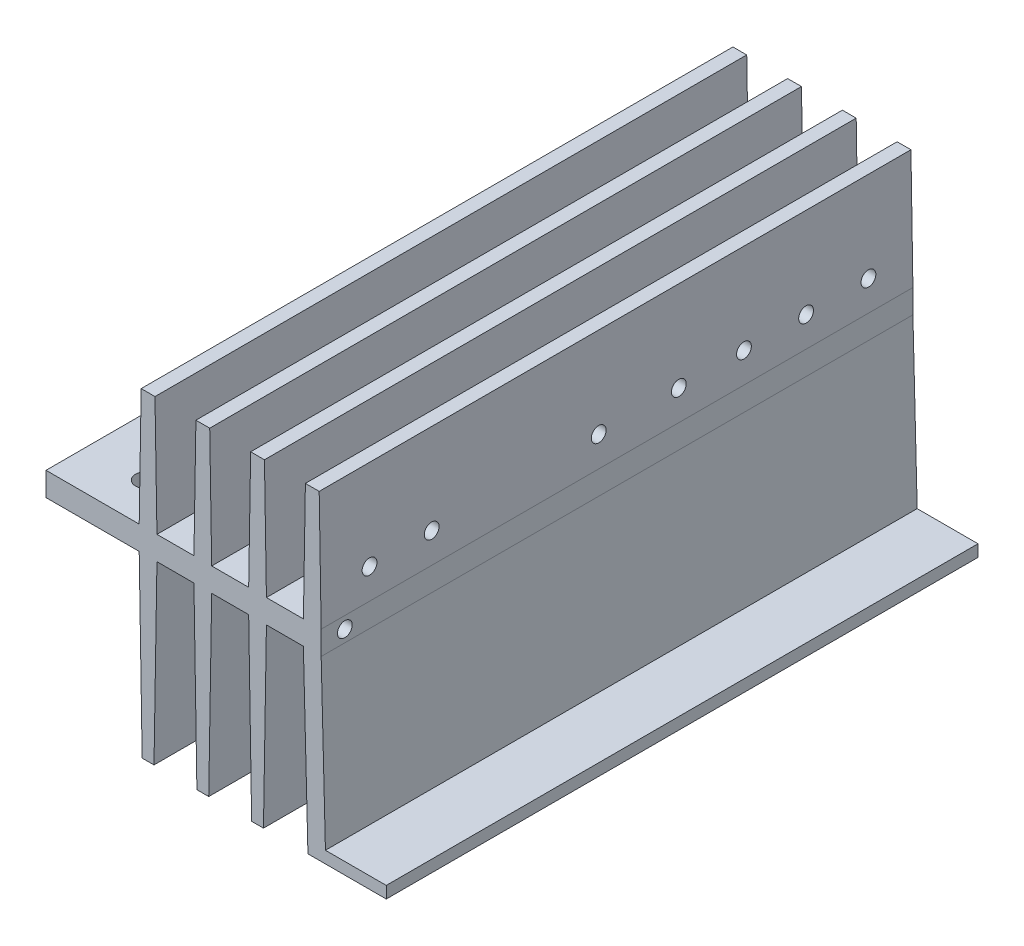
SolidWorks part; units mm, degrees
ref_plane "Front Plane" through (0, 0, 0) normal (0, 0, 1) x (1, 0, 0)
ref_plane "Top Plane" through (0, 0, 0) normal (0, 1, 0) x (1, 0, 0)
ref_plane "Right Plane" through (0, 0, 0) normal (1, 0, 0) x (0, 0, -1)
sketch "Skica1" plane through (0, 0, 0) normal (0, 0, 1) x (1, 0, 0)
  line L0 (7.579, 64.9717) -> (122.579, 64.9717) construction
  line L1 (7.2899, 64.6896) -> (122.2899, 64.6896) construction
  line L2 (64.7899, 64.6896) -> (64.7899, 137.3686) construction
  line L3 (111.2899, 94.6896) -> (18.2899, 94.6896)
  line L4 (18.2899, 98.6896) -> (111.2899, 98.6896)
  line L5 (18.2899, 94.6896) -> (17.5681, 66.6896)
  line L6 (17.5681, 66.6896) -> (7.2899, 66.6896)
  line L7 (7.2899, 66.6896) -> (7.2899, 64.6896)
  line L8 (7.2899, 64.6896) -> (20.5245, 64.6896)
  line L9 (20.5245, 64.6896) -> (21.298, 94.6896)
  line L10 (18.2899, 94.6896) -> (18.2899, 98.6896)
  line L11 (18.2899, 98.6896) -> (18.7899, 128.6896)
  line L12 (18.7899, 128.6896) -> (20.7899, 128.6896)
  line L13 (20.7899, 128.6896) -> (21.2899, 98.6896)
  line L14 (19.7899, 98.6896) -> (19.7899, 132.7731) construction
  line L15 (27.5399, 98.6896) -> (28.0399, 128.6896)
  line L16 (28.0399, 128.6896) -> (30.0399, 128.6896)
  line L17 (30.0399, 128.6896) -> (30.5399, 98.6896)
  line L18 (36.7899, 98.6896) -> (37.2899, 128.6896)
  line L19 (37.2899, 128.6896) -> (39.2899, 128.6896)
  line L20 (39.2899, 128.6896) -> (39.7899, 98.6896)
  line L21 (46.0399, 98.6896) -> (46.5399, 128.6896)
  line L22 (46.5399, 128.6896) -> (48.5399, 128.6896)
  line L23 (48.5399, 128.6896) -> (49.0399, 98.6896)
  line L24 (18.2899, 96.6896) -> (15.4654, 96.6896) construction
  line L25 (48.5399, 64.6896) -> (49.0399, 94.6896)
  line L26 (46.0399, 94.6896) -> (46.5399, 64.6896)
  line L27 (46.5399, 64.6896) -> (48.5399, 64.6896)
  line L28 (39.2899, 64.6896) -> (39.7899, 94.6896)
  line L29 (37.2899, 64.6896) -> (39.2899, 64.6896)
  line L30 (36.7899, 94.6896) -> (37.2899, 64.6896)
  line L31 (30.0399, 64.6896) -> (30.5399, 94.6896)
  line L32 (28.0399, 64.6896) -> (30.0399, 64.6896)
  line L33 (27.5399, 94.6896) -> (28.0399, 64.6896)
  line L34 (111.2899, 96.6896) -> (114.1145, 96.6896) construction
  line L35 (109.7899, 98.6896) -> (109.7899, 132.7731) construction
  line L36 (102.0399, 94.6896) -> (101.5399, 64.6896)
  line L37 (101.5399, 64.6896) -> (99.5399, 64.6896)
  line L38 (99.5399, 64.6896) -> (99.0399, 94.6896)
  line L39 (92.7899, 94.6896) -> (92.2899, 64.6896)
  line L40 (92.2899, 64.6896) -> (90.2899, 64.6896)
  line L41 (90.2899, 64.6896) -> (89.7899, 94.6896)
  line L42 (83.0399, 64.6896) -> (81.0399, 64.6896)
  line L43 (83.5399, 94.6896) -> (83.0399, 64.6896)
  line L44 (81.0399, 64.6896) -> (80.5399, 94.6896)
  line L45 (81.0399, 128.6896) -> (80.5399, 98.6896)
  line L46 (83.0399, 128.6896) -> (81.0399, 128.6896)
  line L47 (83.5399, 98.6896) -> (83.0399, 128.6896)
  line L48 (90.2899, 128.6896) -> (89.7899, 98.6896)
  line L49 (92.2899, 128.6896) -> (90.2899, 128.6896)
  line L50 (92.7899, 98.6896) -> (92.2899, 128.6896)
  line L51 (99.5399, 128.6896) -> (99.0399, 98.6896)
  line L52 (101.5399, 128.6896) -> (99.5399, 128.6896)
  line L53 (102.0399, 98.6896) -> (101.5399, 128.6896)
  line L54 (108.7899, 128.6896) -> (108.2899, 98.6896)
  line L55 (110.7899, 128.6896) -> (108.7899, 128.6896)
  line L56 (111.2899, 98.6896) -> (110.7899, 128.6896)
  line L57 (111.2899, 94.6896) -> (111.2899, 98.6896)
  line L58 (109.0553, 64.6896) -> (108.2819, 94.6896)
  line L59 (122.2899, 64.6896) -> (109.0553, 64.6896)
  line L60 (122.2899, 66.6896) -> (122.2899, 64.6896)
  line L61 (112.0118, 66.6896) -> (122.2899, 66.6896)
  line L62 (111.2899, 94.6896) -> (112.0118, 66.6896)
  point P46 (64.7899, 94.6896)
  point P47 (64.7899, 98.6896)
  dimension "D1" = 115
  dimension "D2" = 115
  dimension "D3" = 3
  dimension "D4" = 2
  dimension "D5" = 1.5
  dimension "D6" = 1
  dimension "D7" = 4
  dimension "D8" = 2
  dimension "D9" = 30
  dimension "D10" = 11
  dimension "D11" = 64
  dimension "D12" = 4
extrude "Přidat vysunutím1" add sketch "Skica1" along normal blind 100 contours L44 L42 L43 L3 | L41 L40 L39 L3 | L38 L37 L36 L3 | L62 L3 L58 L59 L60 L61 | L4 L56 L55 L54 | L4 L53 L52 L51 | L4 L50 L49 L48 | L4 L47 L46 L45 | L3 L57 L4 L10 | L17 L16 L15 L4 | L20 L19 L18 L4 | L23 L22 L21 L4 | L13 L12 L11 L4 | L8 L9 L3 L5 L6 L7 | L3 L33 L32 L31 | L3 L30 L29 L28 | L26 L27 L25 L3
sketch "Skica2" plane through (0, 0, 100) normal (0, 0, 1) x (1, 0, 0)
  line L0 (18.7899, 128.6896) -> (20.7899, 128.6896) construction
  line L1 (8.3667, 139.0565) -> (129.8572, 139.0565)
  line L2 (8.3667, 139.0565) -> (8.3667, 118.6896)
  line L3 (8.3667, 118.6896) -> (129.8572, 118.6896)
  line L4 (129.8572, 139.0565) -> (129.8572, 118.6896)
  dimension "D1" = 10
extrude "Odebrat vysunutím1" cut sketch "Skica2" against normal through all
sketch "Skica3" plane through (0, 0, 100) normal (0, 0, 1) x (1, 0, 0)
  line L0 (122.2899, 66.6896) -> (122.2899, 64.6896) construction
  line L1 (64.7899, 37.8301) -> (-3.1886, 37.8301)
  line L2 (64.7899, 37.8301) -> (64.7899, 121.3997)
  line L3 (64.7899, 121.3997) -> (-3.1886, 121.3997)
  line L4 (-3.1886, 37.8301) -> (-3.1886, 121.3997)
  dimension "D1" = 57.5
extrude "Odebrat vysunutím2" cut sketch "Skica3" against normal through all
sketch "Skica4" plane through (111.2899, 0, 0) normal (1, 0, 0) x (0, 0, -1)
  line L0 (0, 103.6896) -> (-100, 103.6896) construction
  line L1 (0, 98.6896) -> (0, 118.6896) construction
  line L2 (-100, 98.6896) -> (-100, 118.6896) construction
  line L3 (-7.43, 103.2796) -> (-7.43, 94.6896) construction
  line L4 (-100, 94.6896) -> (0, 94.6896) construction
  line L5 (-17.97, 103.2796) -> (-17.97, 94.6896) construction
  line L6 (-28.47, 103.2796) -> (-28.47, 94.6896) construction
  line L7 (-53.01, 103.2796) -> (-53.01, 94.6896) construction
  line L8 (-81.24, 103.2796) -> (-81.24, 94.6896) construction
  line L9 (-91.74, 103.2796) -> (-91.74, 94.6896) construction
  line L10 (15, 122.6896) -> (-112, 122.6896) construction
  circle A0 centre (-91.74, 103.6896) radius 1.25
  circle A1 centre (-81.24, 103.6896) radius 1.25
  circle A2 centre (-53.01, 103.6896) radius 1.25
  circle A3 centre (-28.47, 103.6896) radius 1.25
  circle A4 centre (-17.97, 103.6896) radius 1.25
  circle A5 centre (-7.43, 103.6896) radius 1.25
  circle A6 centre (-39.47, 103.6896) radius 1.25
  dimension "D2" = 2.5
  dimension "D3" = 2.5
  dimension "D4" = 2.5
  dimension "D5" = 2.5
  dimension "D6" = 2.5
  dimension "D7" = 2.5
  dimension "D8" = 2.5
  dimension "D9" = 11
  dimension "D1" = 19
extrude "Odebrat vysunutím3" cut sketch "Skica4" against normal blind 5
sketch "Skica5" plane through (111.2899, 0, 0) normal (1, 0, 0) x (0, 0, -1)
  circle A0 centre (-96, 96.6896) radius 1.25
  dimension "D1" = 2.5
extrude "Odebrat vysunutím4" cut sketch "Skica5" against normal blind 16
sketch "Skica6" plane through (0, 94.6896, 0) normal (0, -1, 0) x (1, 0, 0)
  line L0 (75.1771, 5) -> (75.1771, 65) construction
  circle A0 centre (74.6771, 93) radius 1.25 construction
  circle A1 centre (75.1771, 5) radius 1.25 construction
  circle A2 centre (74.6771, 93) radius 1.25
  circle A3 centre (75.1771, 5) radius 1.25
  circle A4 centre (75.1771, 65) radius 1.25
  dimension "D1" = 2.5
  dimension "D2" = 60
extrude "Odebrat vysunutím5" cut sketch "Skica6" against normal blind 5
sketch "Skica7" plane through (0, 94.6896, 0) normal (0, -1, 0) x (1, 0, 0)
  circle A0 centre (75.1771, 5) radius 1.75
  circle A1 centre (74.6771, 93) radius 1.75
  dimension "D1" = 3.5
  dimension "D2" = 3.5
extrude "Odebrat vysunutím6" cut sketch "Skica7" against normal blind 10
